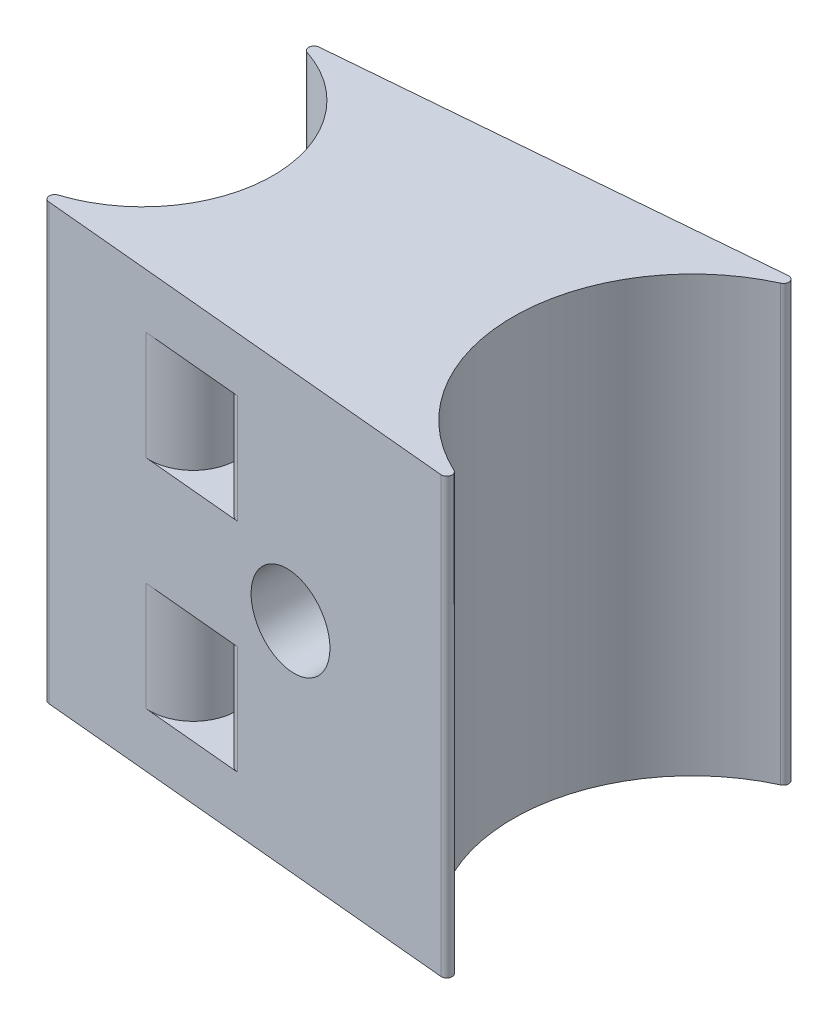
SolidWorks part; units mm, degrees
ref_plane "Front Plane" through (0, 0, 0) normal (0, 0, 1) x (1, 0, 0)
ref_plane "Top Plane" through (0, 0, 0) normal (0, 1, 0) x (1, 0, 0)
ref_plane "Right Plane" through (0, 0, 0) normal (1, 0, 0) x (0, 0, -1)
sketch "Sketch1" plane through (0, 0, 0) normal (0, 1, 0) x (1, 0, 0)
  line L0 (1.9333, 6.1857) -> (21.8401, 7.8751)
  line L1 (1.8834, -6.201) -> (21.7759, -8.051)
  arc A0 (1.8303, -5.714) -> (1.8763, 5.6991) centre (0, 0) ccw
  arc A1 (21.9654, 7.3987) -> (21.905, -7.5756) centre (25.3998, -0.1024) ccw
  arc A2 (21.8401, 7.8751) -> (21.9654, 7.3987) centre (21.8613, 7.626) cw
  arc A3 (21.7759, -8.051) -> (21.905, -7.5756) centre (21.7991, -7.8021) ccw
  arc A4 (1.8834, -6.201) -> (1.8303, -5.714) centre (1.9065, -5.9521) cw
  arc A5 (1.9333, 6.1857) -> (1.8763, 5.6991) centre (1.9545, 5.9365) ccw
  dimension "D1" = 25.4
  dimension "D2" = 0.25
  dimension "D3" = 6
  dimension "D4" = 8.25
extrude "Boss-Extrude1" add sketch "Sketch1" along normal blind 20
sketch "Sketch2" plane through (0, 0, 0) normal (0, 0, 1) x (1, 0, 0)
  line L0 (10, 15) -> (10, 5) construction
  line L1 (9, 17.5) -> (11, 17.5)
  line L2 (9, 17.5) -> (9, 12.5)
  line L3 (9, 12.5) -> (11, 12.5)
  line L4 (11, 17.5) -> (11, 12.5)
  line L5 (9, 17.5) -> (11, 12.5) construction
  line L6 (9, 12.5) -> (11, 17.5) construction
  line L7 (9, 7.5) -> (11, 7.5)
  line L8 (9, 7.5) -> (9, 2.5)
  line L9 (9, 2.5) -> (11, 2.5)
  line L10 (11, 7.5) -> (11, 2.5)
  line L11 (9, 7.5) -> (11, 2.5) construction
  line L12 (9, 2.5) -> (11, 7.5) construction
  line L13 (6, 20) -> (17.1498, 20) construction
  line L14 (10, 10) -> (-4.654, 10) construction
  line L15 (1.8834, 20) -> (1.8834, 0) construction
  line L16 (17.1498, 20) -> (11.5749, 20) construction
  line L17 (17.1498, 20) -> (17.1498, 0) construction
  circle A0 centre (14.1498, 10) radius 2
  point P0 (10, 15)
  point P5 (10, 5)
  point P12 (1.8834, 10)
  point P25 (0, 0)
  point P26 (11.524, 13.0365)
  dimension "D5" = 4
  dimension "D1" = 3
  dimension "D2" = 10
  dimension "D3" = 5
  dimension "D4" = 2
  dimension "D6" = 3
extrude "Cut-Extrude1" cut sketch "Sketch2" against normal through all and the other way through all
fillet "Fillet1" radius 2 4 edges at (9, 5, -6.7854) (9, 15, -6.7854) (9, 5, 6.8629) (9, 15, 6.8629)
fillet "Fillet2" radius 0.5 4 edges at (11, 15, -6.9551) (11, 5, -6.9551) (11, 5, 7.0489) (11, 15, 7.0489)
